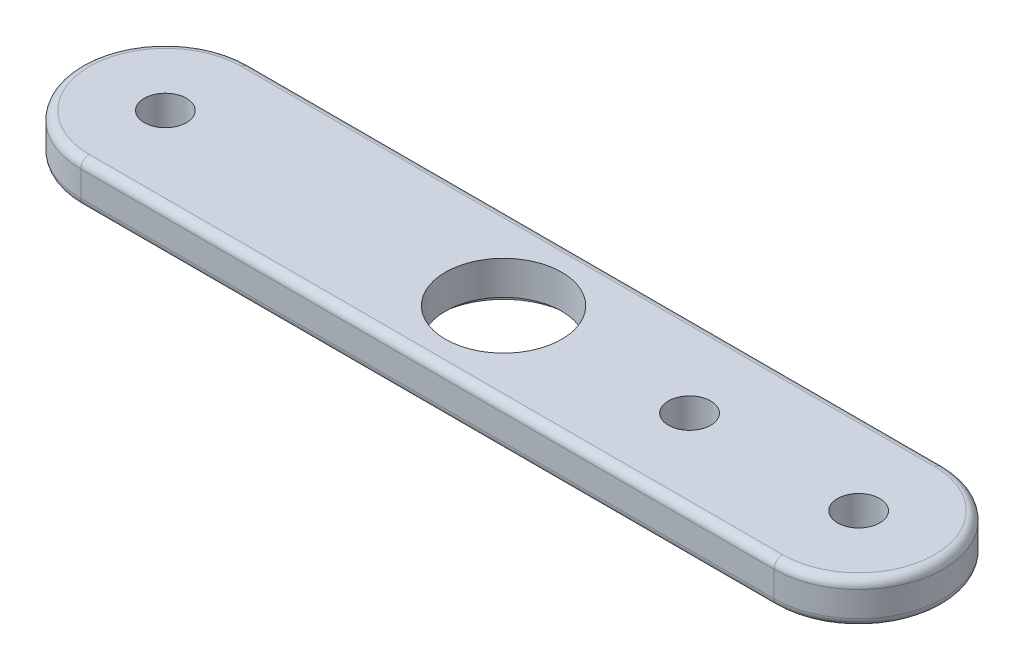
SolidWorks part; units mm, degrees
material "Plain Carbon Steel"
ref_plane "Front Plane" through (0, 0, 0) normal (0, 0, 1) x (1, 0, 0)
ref_plane "Top Plane" through (0, 0, 0) normal (0, 1, 0) x (1, 0, 0)
ref_plane "Right Plane" through (0, 0, 0) normal (1, 0, 0) x (0, 0, -1)
sketch "Sketch1" plane through (0, 0, 0) normal (0, 1, 0) x (1, 0, 0)
  line L1 (64.77, -12.7) -> (-64.77, -12.7)
  line L2 (64.77, -12.7) -> (64.77, 12.7)
  line L3 (64.77, 12.7) -> (-64.77, 12.7)
  line L4 (-64.77, -12.7) -> (-64.77, 12.7)
  line L5 (64.77, -12.7) -> (-64.77, 12.7) construction
  line L6 (64.77, 12.7) -> (-64.77, -12.7) construction
  point P0 (0, 0)
  dimension "D1" = 25.4
  dimension "D2" = 129.54
extrude "Boss-Extrude1" add sketch "Sketch1" along normal blind 6.35
sketch "Sketch2" plane through (0, 6.35, 0) normal (0, 1, 0) x (1, 0, 0)
  line L0 (-64.77, 0) -> (64.77, 0) construction
  line L1 (-64.77, 12.7) -> (-64.77, -12.7) construction
  line L2 (64.77, -12.7) -> (64.77, 12.7) construction
  line L4 (26.67, 3.175) -> (52.07, 3.175) construction
  line L5 (26.67, 3.175) -> (26.67, -3.175) construction
  line L6 (26.67, -3.175) -> (52.07, -3.175) construction
  line L7 (52.07, 3.175) -> (52.07, -3.175) construction
  circle A0 centre (-52.07, 0) radius 3.175
  circle A1 centre (26.67, 0) radius 3.175
  circle A2 centre (52.07, 0) radius 3.175
  arc A4 (26.67, 3.175) -> (26.67, -3.175) centre (26.67, 0) ccw construction
  arc A5 (52.07, -3.175) -> (52.07, 3.175) centre (52.07, 0) ccw construction
  circle A6 centre (-1.27, 0) radius 8.7313
  dimension "D1" = 3.175
  dimension "D8" = 17.4625
  dimension "D3" = 12.7
  dimension "D5" = 50.8
  dimension "D6" = 25.4
  dimension "D7" = 27.94
extrude "Cut-Extrude1" cut sketch "Sketch2" against normal through all
sketch "Sketch3" plane through (0, 0, 0) normal (0, -1, 0) x (-1, 0, 0)
  circle A0 centre (1.27, 0) radius 10.16
  circle A1 centre (1.27, 0) radius 8.7313 construction
  dimension "D1" = 20.32
extrude "Cut-Extrude2" cut sketch "Sketch3" against normal blind 1.27
sketch "Sketch5" plane through (0, 6.35, 0) normal (0, 1, 0) x (1, 0, 0)
  line L0 (-64.77, 12.7) -> (-64.77, -12.7) construction
  line L1 (64.77, -12.7) -> (64.77, 12.7) construction
  circle A0 centre (-52.07, 0) radius 12.7
  circle A1 centre (52.07, 0) radius 12.7
  line M6 (64.77, -12.7) -> (64.77, 12.7)
  line M8 (-64.77, 12.7) -> (-64.77, -12.7)
  line M10 (-64.77, -12.7) -> (64.77, -12.7)
  line M11 (64.77, 12.7) -> (-64.77, 12.7)
extrude "Cut-Extrude3" cut sketch "Sketch5" against normal through all contours A0 M11 M8 | A0 M8 M10 | A1 M10 M6 | A1 M6 M11
fillet "Fillet1" radius 1.27 8 edges at (0, 0, -12.7) (0, 6.35, -12.7) (0, 0, 12.7) (0, 6.35, 12.7) (-64.77, 0, 0) (64.77, 0, 0) (-64.77, 6.35, 0) (64.77, 6.35, 0)
